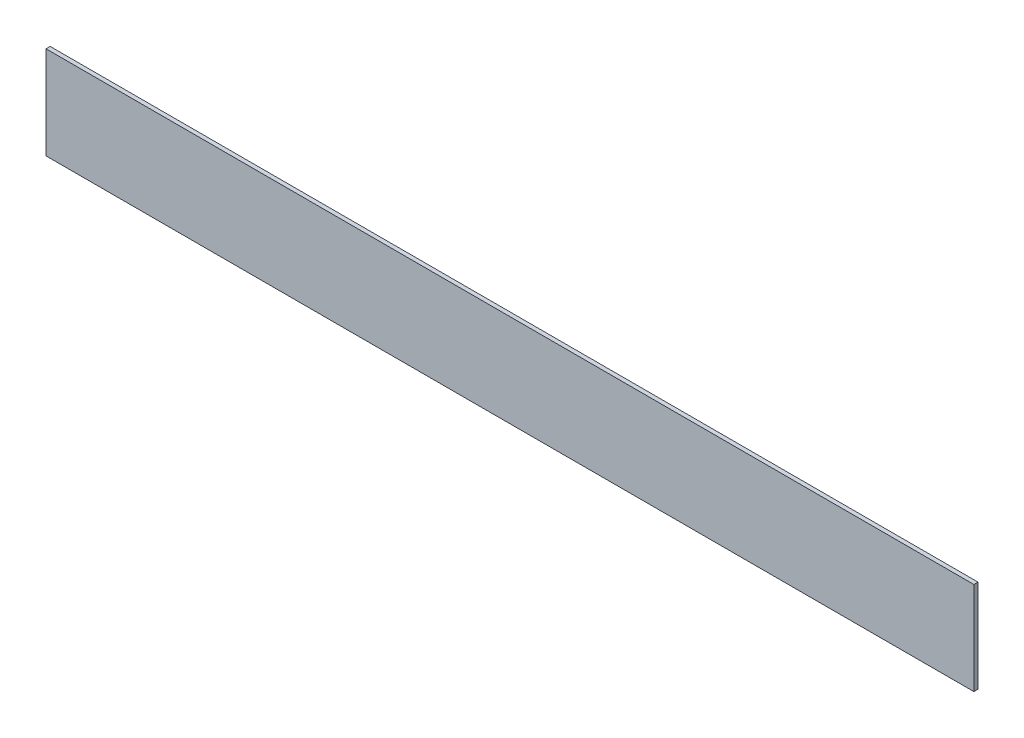
SolidWorks part; units mm, degrees
material "1345 Alloy"
ref_plane "Front Plane" through (0, 0, 0) normal (0, 0, 1) x (1, 0, 0)
ref_plane "Top Plane" through (0, 0, 0) normal (0, 1, 0) x (1, 0, 0)
ref_plane "Right Plane" through (0, 0, 0) normal (1, 0, 0) x (0, 0, -1)
sketch "Sketch1" plane through (0, 0, 0) normal (0, 0, 1) x (1, 0, 0)
  line L1 (-225, 22.5) -> (225, 22.5)
  line L2 (-225, 22.5) -> (-225, -22.5)
  line L3 (-225, -22.5) -> (225, -22.5)
  line L4 (225, 22.5) -> (225, -22.5)
  line L5 (-225, 22.5) -> (225, -22.5) construction
  line L6 (-225, -22.5) -> (225, 22.5) construction
  point P0 (0, 0)
  dimension "D1" = 450
  dimension "D2" = 45
extrude "Boss-Extrude1" add sketch "Sketch1" along normal blind 2
